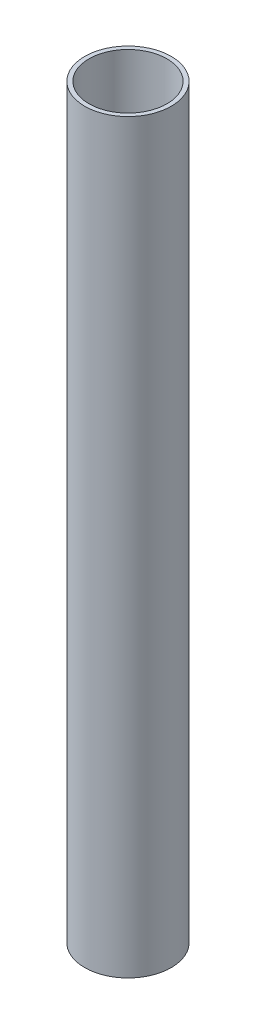
SolidWorks part; units mm, degrees
material "3.3547 (EN-AW 5083)"
ref_plane "Front Plane" through (0, 0, 0) normal (0, 0, 1) x (1, 0, 0)
ref_plane "Top Plane" through (0, 0, 0) normal (0, 1, 0) x (1, 0, 0)
ref_plane "Right Plane" through (0, 0, 0) normal (1, 0, 0) x (0, 0, -1)
sketch "Sketch1" plane through (0, 0, 0) normal (0, 1, 0) x (1, 0, 0)
  circle A0 centre (0, 0) radius 11.5
  circle A1 centre (0, 0) radius 12.75
  dimension "D1" = 25.5
  dimension "D2" = 23
extrude "Boss-Extrude1" add sketch "Sketch1" along normal mid plane 220
